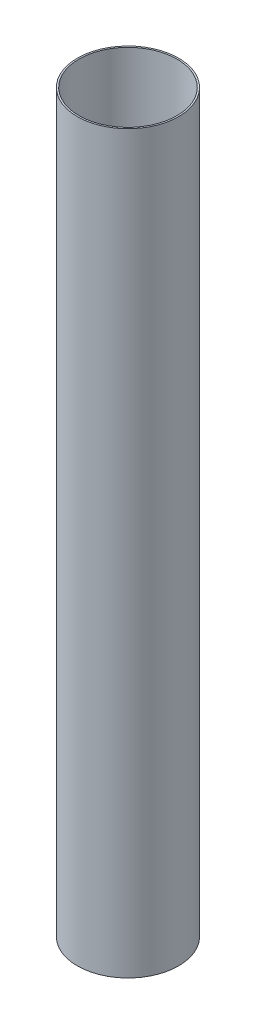
SolidWorks part; units mm, degrees
ref_plane "Front Plane" through (0, 0, 0) normal (0, 0, 1) x (1, 0, 0)
ref_plane "Top Plane" through (0, 0, 0) normal (0, 1, 0) x (1, 0, 0)
ref_plane "Right Plane" through (0, 0, 0) normal (1, 0, 0) x (0, 0, -1)
sketch "Sketch1" plane through (0, 0, 0) normal (0, 1, 0) x (1, 0, 0)
  circle A0 centre (0, 0) radius 78.5
  circle A1 centre (0, 0) radius 76
extrude "Boss-Extrude1" add sketch "Sketch1" along normal blind 1140
